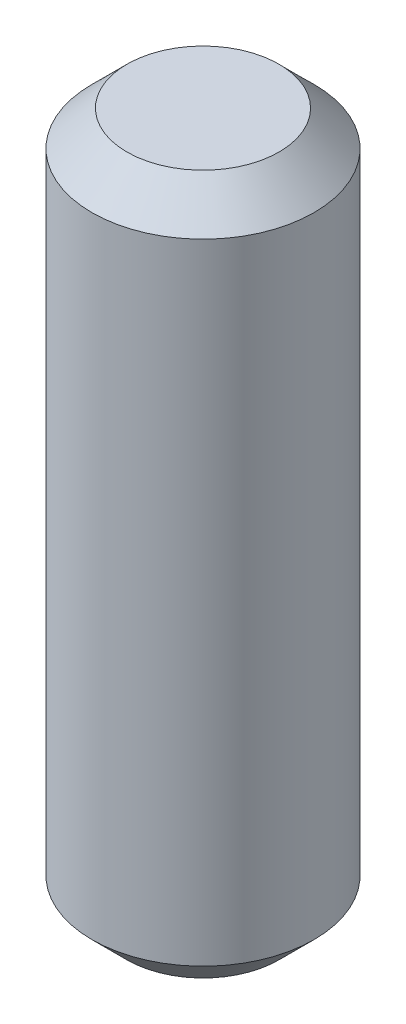
SolidWorks part; units mm, degrees
ref_plane "Front Plane" through (0, 0, 0) normal (0, 0, 1) x (1, 0, 0)
ref_plane "Top Plane" through (0, 0, 0) normal (0, 1, 0) x (1, 0, 0)
ref_plane "Right Plane" through (0, 0, 0) normal (1, 0, 0) x (0, 0, -1)
sketch "Sketch1" plane through (0, 0, 0) normal (0, 1, 0) x (1, 0, 0)
  circle A0 centre (0, 0) radius 1.5875
  dimension "D1" = 3.175
extrude "Boss-Extrude1" add sketch "Sketch1" along normal blind 10
chamfer "Chamfer1" distance 0.5 angle 45 1 edges at (0, 10, 1.5875)
chamfer "Chamfer2" distance 0.5 angle 45 1 edges at (0, 0, 1.5875)
